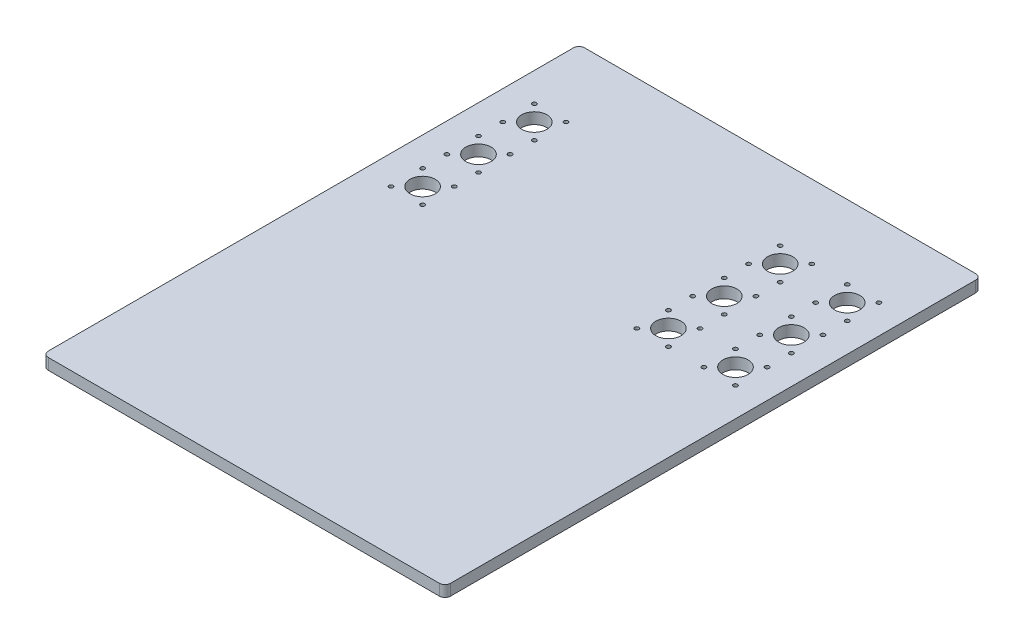
SolidWorks part; units mm, degrees
ref_plane "Front Plane" through (0, 0, 0) normal (0, 0, 1) x (1, 0, 0)
ref_plane "Top Plane" through (0, 0, 0) normal (0, 1, 0) x (1, 0, 0)
ref_plane "Right Plane" through (0, 0, 0) normal (1, 0, 0) x (0, 0, -1)
sketch "Sketch2" plane through (0, 0, 0) normal (0, 1, 0) x (1, 0, 0)
  line L1 (-228.6, -304.8) -> (228.6, -304.8)
  line L2 (-228.6, -304.8) -> (-228.6, 304.8)
  line L3 (-228.6, 304.8) -> (228.6, 304.8)
  line L4 (228.6, -304.8) -> (228.6, 304.8)
  line L5 (-228.6, -304.8) -> (228.6, 304.8) construction
  line L6 (-228.6, 304.8) -> (228.6, -304.8) construction
  point P0 (0, 0)
  dimension "D1" = 457.2
  dimension "D2" = 609.6
extrude "Boss-Extrude1" add sketch "Sketch2" along normal blind 12.7
sketch "Sketch3" plane through (0, 12.7, 0) normal (0, 1, 0) x (1, 0, 0)
  line L0 (-228.6, 203.2) -> (228.6, 203.2) construction
  line L1 (-228.6, 304.8) -> (-228.6, -304.8) construction
  line L2 (228.6, -304.8) -> (228.6, 304.8) construction
  line L3 (228.6, 304.8) -> (-228.6, 304.8) construction
  line L4 (-195.7591, 221.1591) -> (-199.3512, 224.7512) construction
  line L5 (0, 304.8) -> (0, -304.8) construction
  line L6 (-228.6, -304.8) -> (228.6, -304.8) construction
  line L7 (-228.6, 171.45) -> (228.6, 171.45) construction
  line L8 (-228.6, 139.7) -> (228.6, 139.7) construction
  line L9 (-38.1, 304.8) -> (-38.1, -304.8) construction
  circle A0 centre (-177.8, 203.2) radius 14.3383
  circle A1 centre (-177.8, 203.2) radius 25.4 construction
  circle A2 centre (-195.7605, 221.1605) radius 2.3813
  circle A3 centre (-159.8395, 221.1605) radius 2.3813
  circle A4 centre (-177.8, 203.2) radius 25.4 construction
  circle A5 centre (-159.8395, 185.2395) radius 2.3813
  circle A6 centre (-177.8, 203.2) radius 25.4 construction
  circle A7 centre (-195.7605, 185.2395) radius 2.3813
  circle A8 centre (-177.8, 203.2) radius 25.4 construction
  circle A9 centre (-177.8, 203.2) radius 25.4 construction
  circle A10 centre (-177.8, 203.2) radius 50.8 construction
  circle A11 centre (177.8, 203.2) radius 50.8 construction
  circle A12 centre (177.8, 203.2) radius 25.4 construction
  circle A13 centre (177.8, 203.2) radius 25.4 construction
  circle A14 centre (177.8, 203.2) radius 25.4 construction
  circle A15 centre (177.8, 203.2) radius 25.4 construction
  circle A16 centre (177.8, 203.2) radius 25.4 construction
  circle A17 centre (195.7605, 185.2395) radius 2.3813
  circle A18 centre (159.8395, 185.2395) radius 2.3813
  circle A19 centre (159.8395, 221.1605) radius 2.3813
  circle A20 centre (195.7605, 221.1605) radius 2.3813
  circle A21 centre (177.8, 203.2) radius 14.3383
  circle A22 centre (177.8, 139.7) radius 25.4 construction
  circle A23 centre (177.8, 139.7) radius 25.4 construction
  circle A24 centre (177.8, 139.7) radius 25.4 construction
  circle A25 centre (177.8, 139.7) radius 25.4 construction
  circle A26 centre (177.8, 139.7) radius 25.4 construction
  circle A27 centre (177.8, 139.7) radius 50.8 construction
  circle A28 centre (-177.8, 139.7) radius 50.8 construction
  circle A29 centre (-177.8, 139.7) radius 25.4 construction
  circle A30 centre (-177.8, 139.7) radius 25.4 construction
  circle A31 centre (-177.8, 139.7) radius 25.4 construction
  circle A32 centre (-177.8, 139.7) radius 25.4 construction
  circle A33 centre (-177.8, 139.7) radius 25.4 construction
  circle A34 centre (177.8, 139.7) radius 14.3383
  circle A35 centre (195.7605, 121.7395) radius 2.3813
  circle A36 centre (159.8395, 121.7395) radius 2.3813
  circle A37 centre (159.8395, 157.6605) radius 2.3813
  circle A38 centre (195.7605, 157.6605) radius 2.3813
  circle A39 centre (-195.7605, 157.6605) radius 2.3813
  circle A40 centre (-159.8395, 157.6605) radius 2.3813
  circle A41 centre (-159.8395, 121.7395) radius 2.3813
  circle A42 centre (-195.7605, 121.7395) radius 2.3813
  circle A43 centre (-177.8, 139.7) radius 14.3383
  circle A44 centre (177.8, 76.2) radius 25.4 construction
  circle A45 centre (177.8, 76.2) radius 25.4 construction
  circle A46 centre (177.8, 76.2) radius 25.4 construction
  circle A47 centre (177.8, 76.2) radius 25.4 construction
  circle A48 centre (177.8, 76.2) radius 25.4 construction
  circle A49 centre (177.8, 76.2) radius 50.8 construction
  circle A50 centre (-177.8, 76.2) radius 50.8 construction
  circle A51 centre (-177.8, 76.2) radius 25.4 construction
  circle A52 centre (-177.8, 76.2) radius 25.4 construction
  circle A53 centre (-177.8, 76.2) radius 25.4 construction
  circle A54 centre (-177.8, 76.2) radius 25.4 construction
  circle A55 centre (-177.8, 76.2) radius 25.4 construction
  circle A56 centre (177.8, 76.2) radius 14.3383
  circle A57 centre (195.7605, 58.2395) radius 2.3813
  circle A58 centre (159.8395, 58.2395) radius 2.3813
  circle A59 centre (159.8395, 94.1605) radius 2.3813
  circle A60 centre (195.7605, 94.1605) radius 2.3813
  circle A61 centre (-195.7605, 94.1605) radius 2.3813
  circle A62 centre (-159.8395, 94.1605) radius 2.3813
  circle A63 centre (-159.8395, 58.2395) radius 2.3813
  circle A64 centre (-195.7605, 58.2395) radius 2.3813
  circle A65 centre (-177.8, 76.2) radius 14.3383
  circle A66 centre (101.6, 76.2) radius 25.4 construction
  circle A67 centre (101.6, 76.2) radius 25.4 construction
  circle A68 centre (101.6, 76.2) radius 25.4 construction
  circle A69 centre (101.6, 76.2) radius 25.4 construction
  circle A70 centre (101.6, 76.2) radius 25.4 construction
  circle A71 centre (101.6, 76.2) radius 50.8 construction
  circle A72 centre (101.6, 139.7) radius 25.4 construction
  circle A73 centre (101.6, 139.7) radius 25.4 construction
  circle A74 centre (101.6, 139.7) radius 25.4 construction
  circle A75 centre (101.6, 139.7) radius 25.4 construction
  circle A76 centre (101.6, 139.7) radius 25.4 construction
  circle A77 centre (101.6, 139.7) radius 50.8 construction
  circle A78 centre (101.6, 203.2) radius 50.8 construction
  circle A79 centre (101.6, 203.2) radius 25.4 construction
  circle A80 centre (101.6, 203.2) radius 25.4 construction
  circle A81 centre (101.6, 203.2) radius 25.4 construction
  circle A82 centre (101.6, 203.2) radius 25.4 construction
  circle A83 centre (101.6, 203.2) radius 25.4 construction
  circle A84 centre (101.6, 76.2) radius 14.3383
  circle A85 centre (119.5605, 58.2395) radius 2.3813
  circle A86 centre (83.6395, 58.2395) radius 2.3813
  circle A87 centre (83.6395, 94.1605) radius 2.3813
  circle A88 centre (119.5605, 94.1605) radius 2.3813
  circle A89 centre (101.6, 139.7) radius 14.3383
  circle A90 centre (119.5605, 121.7395) radius 2.3813
  circle A91 centre (83.6395, 121.7395) radius 2.3813
  circle A92 centre (83.6395, 157.6605) radius 2.3813
  circle A93 centre (119.5605, 157.6605) radius 2.3813
  circle A94 centre (119.5605, 185.2395) radius 2.3813
  circle A95 centre (83.6395, 185.2395) radius 2.3813
  circle A96 centre (83.6395, 221.1605) radius 2.3813
  circle A97 centre (119.5605, 221.1605) radius 2.3813
  circle A98 centre (101.6, 203.2) radius 14.3383
  point P25 (-177.8, 203.2)
  point P81 (-177.8, 139.7)
  point P116 (-177.8, 76.2)
  point P167 (101.6, 76.2)
  point P168 (101.6, 139.7)
  point P169 (101.6, 203.2)
  dimension "D2" = 28.6766
  dimension "D3" = 4.7625
  dimension "D6" = 50.8
  dimension "D7" = 101.6
  dimension "D8" = 355.6
  dimension "D9" = 50.8
  dimension "D10" = 31.75
  dimension "D1" = 101.6
  dimension "D5" = 45
  dimension "D11" = 38.1
  dimension "D4" = 4
extrude "Cut-Extrude1" cut sketch "Sketch3" against normal through all
fillet "Fillet1" radius 6.35 4 edges at (-228.6, 6.35, 304.8) (228.6, 6.35, 304.8) (-228.6, 6.35, -304.8) (228.6, 6.35, -304.8)
